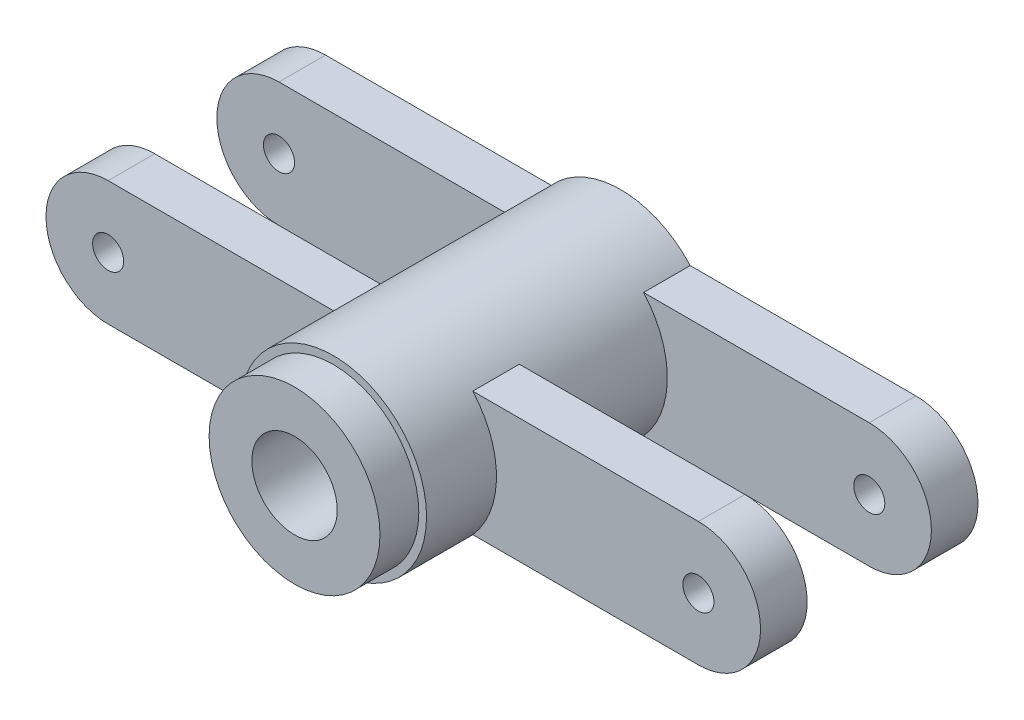
SolidWorks part; units mm, degrees
ref_plane "前视基准面" through (0, 0, 0) normal (0, 0, 1) x (1, 0, 0)
ref_plane "上视基准面" through (0, 0, 0) normal (0, 1, 0) x (1, 0, 0)
ref_plane "右视基准面" through (0, 0, 0) normal (1, 0, 0) x (0, 0, -1)
sketch "草图1" plane through (0, 0, 0) normal (0, 0, 1) x (1, 0, 0)
  circle A0 centre (0, 0) radius 6
  dimension "D1" = 12
extrude "凸台-拉伸1" add sketch "草图1" along normal blind 11
sketch "草图2" plane through (0, 0, 0) normal (0, 0, 1) x (1, 0, 0)
  line L0 (-19, 4) -> (19, 4)
  line L1 (-19, -4) -> (19, -4)
  arc A0 (-19, 4) -> (-19, -4) centre (-19, 0) ccw
  arc A1 (19, -4) -> (19, 4) centre (19, 0) ccw
  dimension "D1" = 8
  dimension "D2" = 8
  dimension "D3" = 19
  dimension "D4" = 19
extrude "凸台-拉伸2" add sketch "草图2" along normal blind 3
sketch "草图3" plane through (0, 0, 11) normal (0, 0, 1) x (1, 0, 0)
  line L0 (-19, 4) -> (19, 4)
  line L1 (-19, -4) -> (19, -4)
  arc A0 (-19, 4) -> (-19, -4) centre (-19, 0) ccw
  arc A1 (19, -4) -> (19, 4) centre (19, 0) ccw
  dimension "D1" = 8
  dimension "D2" = 8
extrude "凸台-拉伸3" add sketch "草图3" along normal blind 3
sketch "草图5" plane through (0, 0, 11) normal (0, 0, 1) x (1, 0, 0)
  circle A0 centre (0, 0) radius 6
  dimension "D1" = 12
extrude "凸台-拉伸4" add sketch "草图5" along normal blind 10
sketch "草图6" plane through (0, 0, 0) normal (0, 0, -1) x (-1, 0, 0)
  circle A0 centre (0, 0) radius 1.5
  dimension "D1" = 3
extrude "切除-拉伸1" cut sketch "草图6" against normal through all
sketch "草图7" plane through (0, 0, 21) normal (0, 0, 1) x (1, 0, 0)
  circle A0 centre (0, 0) radius 6
  circle A1 centre (0, 0) radius 5.5
  dimension "D1" = 12
  dimension "D2" = 11
extrude "切除-拉伸2" cut sketch "草图7" against normal blind 2.5
sketch "草图8" plane through (0, 0, 14) normal (0, 0, 1) x (1, 0, 0)
  circle A0 centre (-19, 0) radius 1
  circle A1 centre (19, 0) radius 1
  dimension "D1" = 2
  dimension "D2" = 2
extrude "切除-拉伸3" cut sketch "草图8" against normal through all
sketch "草图9" plane through (0, 0, 21) normal (0, 0, 1) x (1, 0, 0)
  circle A0 centre (0, 0) radius 2.75
  dimension "D1" = 5.5
extrude "切除-拉伸4" cut sketch "草图9" against normal blind 5
